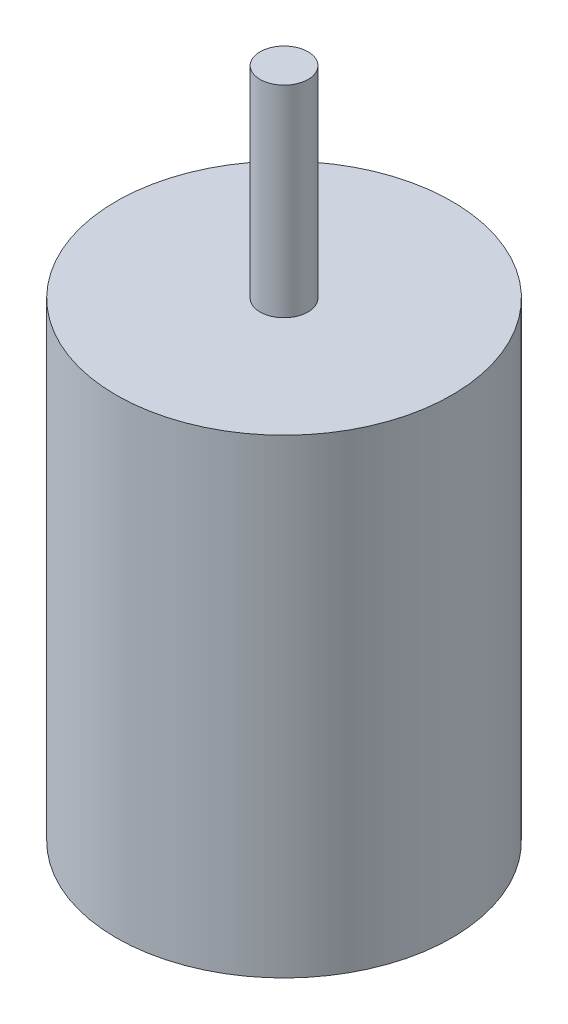
SolidWorks part; units mm, degrees
ref_plane "Front Plane" through (0, 0, 0) normal (0, 0, 1) x (1, 0, 0)
ref_plane "Top Plane" through (0, 0, 0) normal (0, 1, 0) x (1, 0, 0)
ref_plane "Right Plane" through (0, 0, 0) normal (1, 0, 0) x (0, 0, -1)
sketch "Sketch1" plane through (0, 0, 0) normal (0, 1, 0) x (1, 0, 0)
  circle A0 centre (0, 0) radius 2.5
  dimension "D1" = 5
extrude "Boss-Extrude1" add sketch "Sketch1" along normal blind 70
sketch "Sketch2" plane through (0, 0, 0) normal (0, 1, 0) x (1, 0, 0)
  circle A0 centre (0, 0) radius 17.5
  dimension "D1" = 35
extrude "Boss-Extrude2" add sketch "Sketch2" along normal blind 49
